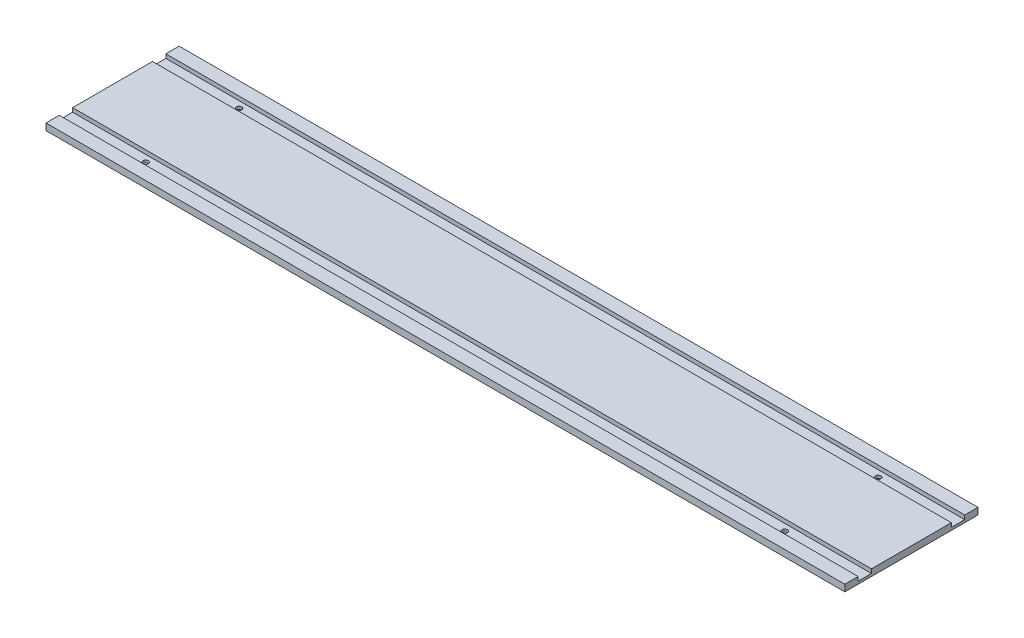
SolidWorks part; units mm, degrees
ref_plane "Front Plane" through (0, 0, 0) normal (0, 0, 1) x (1, 0, 0)
ref_plane "Top Plane" through (0, 0, 0) normal (0, 1, 0) x (1, 0, 0)
ref_plane "Right Plane" through (0, 0, 0) normal (1, 0, 0) x (0, 0, -1)
sketch "Sketch1" plane through (0, 0, 0) normal (0, 0, 1) x (1, 0, 0)
  line L0 (0, 0) -> (600, 0)
  line L1 (600, 0) -> (600, 5)
  line L2 (600, 5) -> (0, 5)
  line L3 (0, 5) -> (0, 0)
  dimension "D1" = 600
  dimension "D2" = 5
extrude "Boss-Extrude1" add sketch "Sketch1" against normal blind 100
sketch "Sketch5" plane through (0, 5, 0) normal (0, 1, 0) x (1, 0, 0)
  line L2 (0, 90) -> (600, 90)
  line L6 (0, 80) -> (600, 80)
  line L8 (0, 90) -> (0, 80)
  line L9 (600, 90) -> (600, 80)
  line L10 (0, 20) -> (0, 10)
  line L11 (600, 20) -> (600, 10)
  line L12 (0, 20) -> (600, 20)
  line L13 (0, 10) -> (600, 10)
extrude "Cut-Extrude1" cut sketch "Sketch5" against normal blind 3
sketch "Sketch6" plane through (0, 5, 0) normal (0, 1, 0) x (1, 0, 0)
  circle A0 centre (60, 85) radius 2
  circle A1 centre (60, 15) radius 2
  circle A2 centre (540, 85) radius 2
  circle A3 centre (540, 15) radius 2
extrude "Cut-Extrude2" cut sketch "Sketch6" against normal through all
